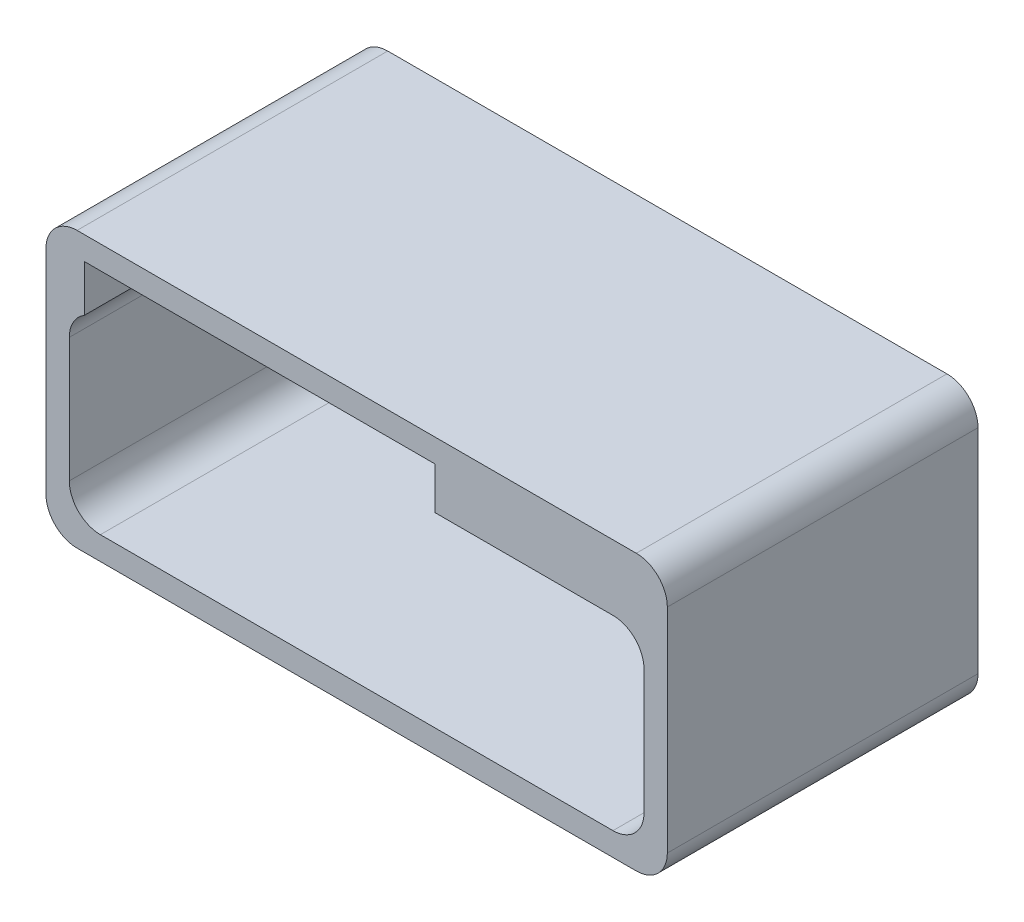
SolidWorks part; units mm, degrees
ref_plane "Front Plane" through (0, 0, 0) normal (0, 0, 1) x (1, 0, 0)
ref_plane "Top Plane" through (0, 0, 0) normal (0, 1, 0) x (1, 0, 0)
ref_plane "Right Plane" through (0, 0, 0) normal (1, 0, 0) x (0, 0, -1)
sketch "Sketch1" plane through (0, 0, 0) normal (0, 0, 1) x (1, 0, 0)
  line L1 (-11.6133, 21.4958) -> (60.3867, 21.4958)
  line L2 (-15.6133, 17.4958) -> (-15.6133, -9.9342)
  line L3 (-11.6133, -13.9342) -> (60.3867, -13.9342)
  line L4 (64.3867, 17.4958) -> (64.3867, -9.9342)
  line L5 (-10.6733, 18.4958) -> (34.4567, 18.4958)
  line L6 (-12.6133, 9.0658) -> (-12.6133, -6.9342)
  line L7 (-8.6133, -10.9342) -> (57.3867, -10.9342)
  line L8 (61.3867, 9.0658) -> (61.3867, -6.9342)
  line L9 (-10.6733, 13.0658) -> (-10.6733, 18.4958)
  line L10 (34.4567, 18.4958) -> (34.4567, 13.0658)
  line L11 (34.4567, 13.0658) -> (57.3867, 13.0658)
  line L12 (-10.6733, 13.0658) -> (-10.6733, 12.4946)
  arc A0 (-12.6133, 9.0658) -> (-10.6733, 12.4946) centre (-8.6133, 9.0658) cw
  arc A1 (-8.6133, -10.9342) -> (-12.6133, -6.9342) centre (-8.6133, -6.9342) cw
  arc A2 (61.3867, -6.9342) -> (57.3867, -10.9342) centre (57.3867, -6.9342) cw
  arc A3 (61.3867, 9.0658) -> (57.3867, 13.0658) centre (57.3867, 9.0658) ccw
  arc A4 (60.3867, -13.9342) -> (64.3867, -9.9342) centre (60.3867, -9.9342) ccw
  arc A5 (-15.6133, 17.4958) -> (-11.6133, 21.4958) centre (-11.6133, 17.4958) cw
  arc A6 (-11.6133, -13.9342) -> (-15.6133, -9.9342) centre (-11.6133, -9.9342) cw
  arc A7 (60.3867, 21.4958) -> (64.3867, 17.4958) centre (60.3867, 17.4958) cw
  dimension "D8" = 4
  dimension "D9" = 4
  dimension "D1" = 3
  dimension "D2" = 3
  dimension "D3" = 3
  dimension "D4" = 3
  dimension "D5" = 74
  dimension "D6" = 24
  dimension "D7" = 29.43
  dimension "D10" = 45.13
  dimension "D11" = 1.94
extrude "Boss-Extrude1" add sketch "Sketch1" along normal blind 40
